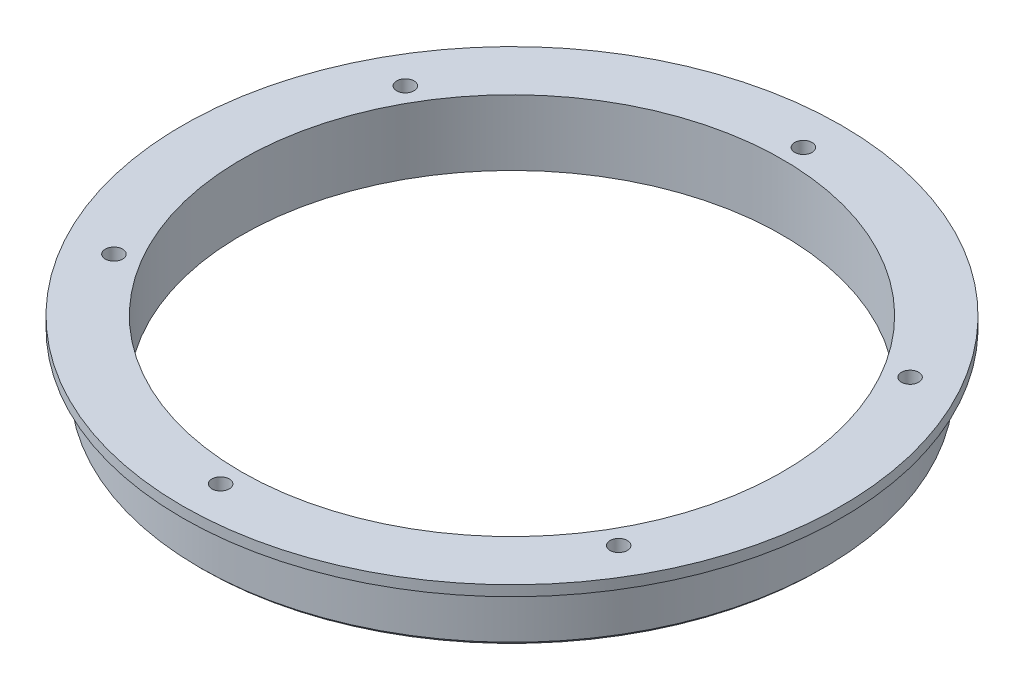
SolidWorks part; units mm, degrees
material "6061 合金"
ref_plane "前视基准面" through (0, 0, 0) normal (0, 0, 1) x (1, 0, 0)
ref_plane "上视基准面" through (0, 0, 0) normal (0, 1, 0) x (1, 0, 0)
ref_plane "右视基准面" through (0, 0, 0) normal (1, 0, 0) x (0, 0, -1)
other "Configuration Table"
sketch "草图1" plane through (0, 0, 0) normal (0, 1, 0) x (1, 0, 0)
  circle A0 centre (0, 0) radius 45
  circle A1 centre (0, 0) radius 39
  dimension "D1" = 90
  dimension "D2" = 6
extrude "凸台-拉伸1" add sketch "草图1" along normal mid plane 7.95
sketch "草图2" plane through (0, 3.975, 0) normal (0, 1, 0) x (1, 0, 0)
  circle A0 centre (0, 0) radius 47.5
  circle A1 centre (0, 0) radius 45 construction
  circle A2 centre (0, 0) radius 39 construction
  circle A3 centre (0, 0) radius 39
  dimension "D1" = 2.5
extrude "凸台-拉伸2" add sketch "草图2" along normal blind 1.5
sketch "草图3" plane through (0, -3.975, 0) normal (0, -1, 0) x (1, 0, 0)
  circle A0 centre (0, 0) radius 42 construction
  circle A1 centre (0, 0) radius 45 construction
  dimension "D1" = 3
hole_wizard "M3 螺纹孔1" positions "草图4" profile "草图5" tap size "M3" standard "GB" end condition through all
sketch "草图4" plane through (0, -3.975, 0) normal (0, -1, 0) x (-1, 0, 0)
  circle A0 centre (0, 0) radius 42 construction
  point P0 (0, 42)
sketch "草图5" plane through (0, -3.975, -42) normal (1, 0, 0) x (0, 0, -1)
  line L0 (0, 0) -> (0, 9.45)
  line L1 (0, 9.45) -> (1.25, 9.45)
  line L2 (1.25, 9.45) -> (1.25, 0.275)
  line L3 (1.25, 0.275) -> (1.525, 0)
  line L5 (1.525, 0) -> (0, 0)
  line L6 (-1.25, 0.275) -> (-1.525, 0) construction
  line L11 (0, -6.35) -> (0, 107.95) construction
  dimension "通孔螺纹孔钻头直径" = 2.5
  dimension "通孔螺纹孔钻头深度" = 9.45
  dimension "近端锥形沉头孔直径" = 3.05
  dimension "近端锥形沉头孔角度" = 90
cosmetic thread "孔螺蚊线1" parameters "D2"=3
pattern_circular "阵列(圆周)1" count 6 over 360 about axis through (0, 0, 0) along (0, 1, 0) of "M3 螺纹孔1"
chamfer "倒角1" distance 0.5 angle 45 1 edges at (0, -3.975, 45)
